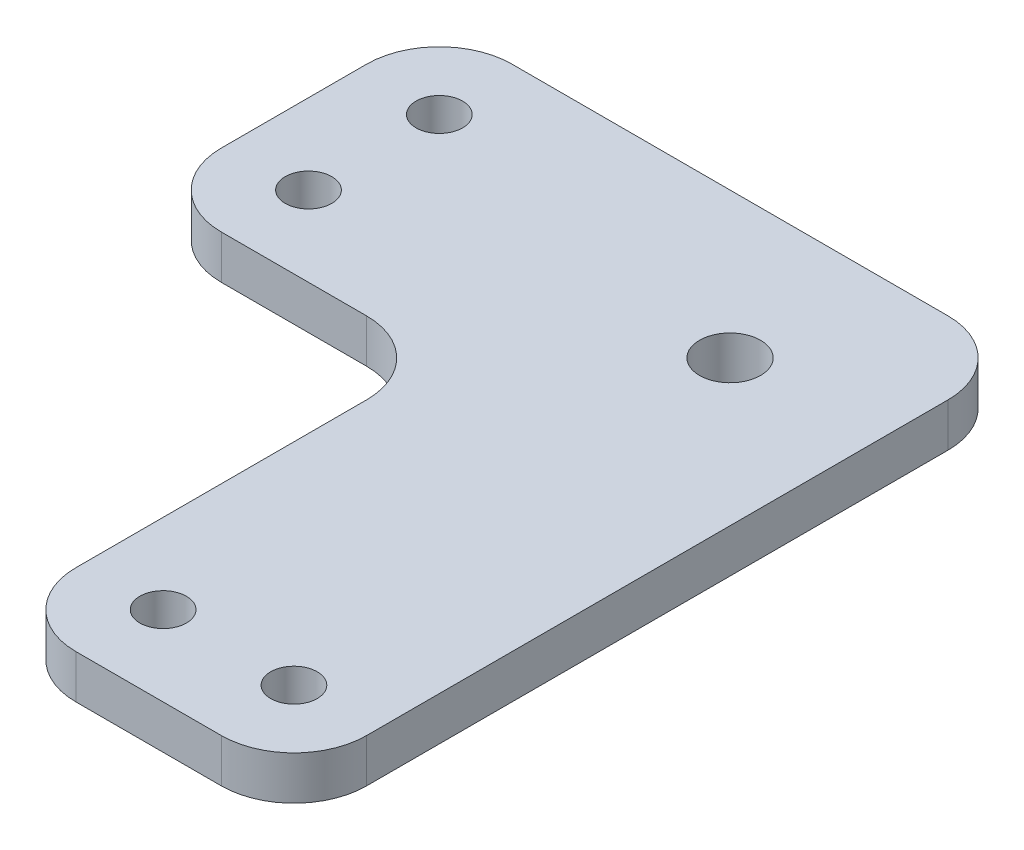
SolidWorks part; units mm, degrees
material "6061-T6 (SS)"
ref_plane "前视基准面" through (0, 0, 0) normal (0, 0, 1) x (1, 0, 0)
ref_plane "上视基准面" through (0, 0, 0) normal (0, 1, 0) x (1, 0, 0)
ref_plane "右视基准面" through (0, 0, 0) normal (1, 0, 0) x (0, 0, -1)
sketch "草图1" plane through (0, 0, 0) normal (0, 1, 0) x (1, 0, 0)
  line L0 (-30, 35) -> (-30, 15)
  line L1 (-10, 15) -> (10, 15) construction
  line L2 (-10, 15) -> (-10, -15) construction
  line L3 (-10, -15) -> (10, -15) construction
  line L4 (10, 15) -> (10, -15) construction
  line L5 (0, -15) -> (0, 15) construction
  line L6 (-10, 0) -> (10, 0) construction
  line L7 (10, 15) -> (-30, 15) construction
  line L8 (10, 15) -> (10, 35) construction
  line L9 (10, 35) -> (-30, 35) construction
  line L10 (-30, 15) -> (-30, 35) construction
  line L11 (10, 15) -> (-30, 35) construction
  line L12 (10, 35) -> (-30, 15) construction
  line L13 (-30, 15) -> (-10, 15)
  line L14 (-10, 15) -> (-10, -15)
  line L15 (-10, -15) -> (10, -15)
  line L16 (10, -15) -> (10, 35)
  line L17 (10, 35) -> (-30, 35)
  point P0 (0, 0)
  point P7 (-10, 25)
  dimension "D1" = 20
  dimension "D2" = 30
  dimension "D3" = 20
  dimension "D4" = 40
extrude "凸台-拉伸1" add sketch "草图1" along normal blind 3
sketch "草图2" plane through (0, 3, 0) normal (0, 1, 0) x (1, 0, 0)
  line L0 (10, -15) -> (10, 35) construction
  line L1 (-10, -15) -> (10, -15) construction
  line L2 (-10, -15) -> (-10, 5) construction
  line L3 (-10, 5) -> (10, 5) construction
  line L4 (10, -15) -> (10, 5) construction
  line L5 (-10, -15) -> (10, 5) construction
  line L6 (-10, 5) -> (10, -15) construction
  line L7 (10, 35) -> (-30, 35) construction
  line L8 (-30, 15) -> (-10, 15) construction
  line L9 (-30, 15) -> (-30, 35) construction
  line L10 (-30, 35) -> (-10, 35) construction
  line L11 (-10, 15) -> (-10, 35) construction
  line L12 (-30, 15) -> (-10, 35) construction
  line L13 (-30, 35) -> (-10, 15) construction
  line L15 (-24.5, 29.5) -> (-15.5, 29.5) construction
  line L16 (-24.5, 29.5) -> (-24.5, 20.5) construction
  line L17 (-24.5, 20.5) -> (-15.5, 20.5) construction
  line L18 (-15.5, 29.5) -> (-15.5, 20.5) construction
  line L19 (-20, 20.5) -> (-20, 29.5) construction
  line L20 (-24.5, 25) -> (-15.5, 25) construction
  line L21 (-4.5, -0.5) -> (4.5, -0.5) construction
  line L22 (-4.5, -0.5) -> (-4.5, -9.5) construction
  line L23 (-4.5, -9.5) -> (4.5, -9.5) construction
  line L24 (4.5, -0.5) -> (4.5, -9.5) construction
  line L25 (0, -9.5) -> (0, -0.5) construction
  line L26 (-4.5, -5) -> (4.5, -5) construction
  circle A0 centre (-24.5, 29.5) radius 1.6
  circle A1 centre (-24.5, 20.5) radius 1.6
  circle A2 centre (-4.5, -9.5) radius 1.6
  circle A3 centre (4.5, -9.5) radius 1.6
  point P4 (0, -5)
  point P12 (-20, 25)
  point P16 (-20, 25)
  point P20 (0, -5)
  dimension "D1" = 20
  dimension "D2" = 20
  dimension "D3" = 9
  dimension "D4" = 9
  dimension "D5" = 9
  dimension "D6" = 9
extrude "切除-拉伸1" cut sketch "草图2" against normal through all
fillet "圆角1" radius 5 6 edges at (10, 1.5, -35) (-30, 1.5, -35) (10, 1.5, 15) (-10, 1.5, 15) (-10, 1.5, -15) (-30, 1.5, -15)
sketch "草图3" plane through (0, 3, 0) normal (0, 1, 0) x (1, 0, 0)
  circle A0 centre (0, 25) radius 10 construction
  circle A1 centre (0, 25) radius 2.1
extrude "切除-拉伸2" cut sketch "草图3" against normal through all
